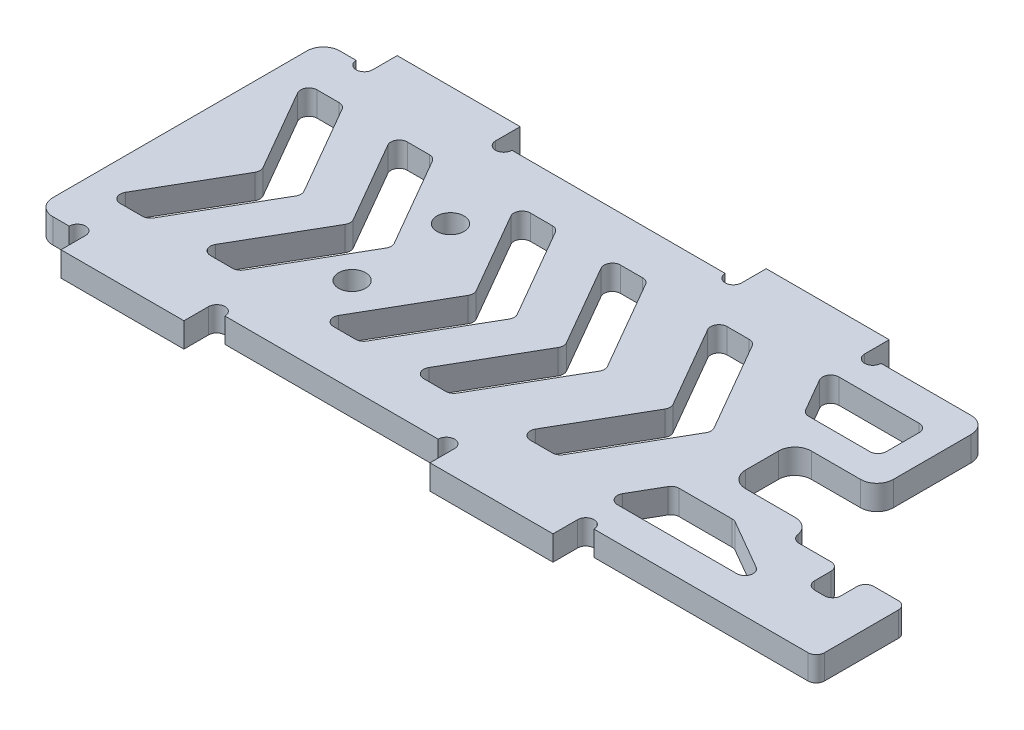
SolidWorks part; units mm, degrees
material "环氧树脂,未充填"
ref_plane "前视基准面" through (0, 0, 0) normal (0, 0, 1) x (1, 0, 0)
ref_plane "上视基准面" through (0, 0, 0) normal (0, 1, 0) x (1, 0, 0)
ref_plane "右视基准面" through (0, 0, 0) normal (1, 0, 0) x (0, 0, -1)
sketch "草图1" plane through (0, 0, 0) normal (0, 1, 0) x (1, 0, 0)
  line L0 (-30, 20.5) -> (-15, 20.5)
  line L1 (-15, 20.5) -> (-15, 17.5)
  line L2 (-15, 17.5) -> (15, 17.5)
  line L3 (15, 17.5) -> (15, 20.5)
  line L4 (15, 20.5) -> (30, 20.5)
  line L5 (30, 20.5) -> (30, 17.5)
  line L6 (30, 17.5) -> (43, 17.5)
  line L7 (45, 15.5) -> (45, -5.5)
  line L8 (46, -6.5) -> (49.9, -6.5)
  line L9 (50.9, -7.5) -> (50.9, -9.5)
  line L10 (51.9, -10.5) -> (53.1, -10.5)
  line L11 (54.1, -9.5) -> (54.1, -7.5)
  line L12 (55.1, -6.5) -> (58.1, -6.5)
  line L13 (59.1, -7.5) -> (59.1, -16.5)
  line L14 (58.1, -17.5) -> (30, -17.5)
  line L15 (30, -17.5) -> (30, -20.5)
  line L16 (30, -20.5) -> (15, -20.5)
  line L17 (15, -20.5) -> (15, -17.5)
  line L18 (15, -17.5) -> (-15, -17.5)
  line L19 (-15, -17.5) -> (-15, -20.5)
  line L20 (-15, -20.5) -> (-30, -20.5)
  line L21 (-30, -20.5) -> (-30, -17.5)
  line L22 (-30, -17.5) -> (-34, -17.5)
  line L23 (-36, -15.5) -> (-36, 15.5)
  line L24 (-34, 17.5) -> (-30, 17.5)
  line L25 (-30, 17.5) -> (-30, 20.5)
  line L26 (-1000, 0) -> (49000, 0) construction
  line L27 (-9, -6) -> (-9, 6) construction
  arc A0 (53.1, -10.5) -> (54.1, -9.5) centre (53.1, -9.5) ccw
  arc A1 (50.9, -9.5) -> (51.9, -10.5) centre (51.9, -9.5) ccw
  arc A2 (59.1, -16.5) -> (58.1, -17.5) centre (58.1, -16.5) cw
  arc A3 (58.1, -6.5) -> (59.1, -7.5) centre (58.1, -7.5) cw
  arc A4 (54.1, -7.5) -> (55.1, -6.5) centre (55.1, -7.5) cw
  arc A5 (45, -5.5) -> (46, -6.5) centre (46, -5.5) ccw
  circle A6 centre (-9, 6) radius 1.65
  circle A7 centre (-9, -6) radius 1.65
  arc A8 (-34, -17.5) -> (-36, -15.5) centre (-34, -15.5) cw
  arc A9 (-36, 15.5) -> (-34, 17.5) centre (-34, 15.5) cw
  arc A10 (43, 17.5) -> (45, 15.5) centre (43, 15.5) cw
  arc A11 (49.9, -6.5) -> (50.9, -7.5) centre (49.9, -7.5) cw
  point P29 (-9, 0)
  point P37 (0, -17.5)
  dimension "D6" = 1
  dimension "D8" = 1
  dimension "D14" = 1
  dimension "D16" = 3.3
  dimension "D18" = 2
  dimension "D19" = 1
  dimension "D1" = 15
  dimension "D2" = 30
  dimension "D3" = 3
  dimension "D4" = 11
  dimension "D5" = 7
  dimension "D7" = 5
  dimension "D9" = 17.5
  dimension "D10" = 6
  dimension "D11" = 15
  dimension "D12" = 5.9
  dimension "D13" = 3.2
  dimension "D15" = 12
  dimension "D17" = 9
  dimension "D20" = 30
  dimension "D21" = 3
  dimension "D22" = 36
  dimension "D23" = 17.5
  dimension "D24" = 15
  dimension "D25" = 0
extrude "凸台-拉伸1" add sketch "草图1" along normal blind 3
sketch "草图2" plane through (0, 3, 0) normal (0, 1, 0) x (1, 0, 0)
  line L0 (-201000, 0) -> (249000, 0) construction
  line L1 (37, -4) -> (45, -4)
  line L2 (35, -2) -> (35, 2)
  line L3 (37, 4) -> (45, 4)
  line L4 (45, -4) -> (45, 4)
  line L5 (35, -4) -> (45, 4) construction
  line L6 (35, 4) -> (45, -4) construction
  line L7 (45, 15.5) -> (45, -5.5) construction
  arc A0 (35, 2) -> (37, 4) centre (37, 2) cw
  arc A1 (37, -4) -> (35, -2) centre (37, -2) cw
  point P0 (40, 0)
  dimension "D3" = 2
  dimension "D1" = 8
  dimension "D2" = 10
extrude "切除-拉伸1" cut sketch "草图2" against normal blind 3
fillet "圆角1" radius 2 2 edges at (45, 1.5, 4) (45, 1.5, -4)
sketch "草图3" plane through (0, 3, 0) normal (0, 1, 0) x (1, 0, 0)
  line L0 (-30, 17.5) -> (-34, 17.5) construction
  line L1 (15, 17.5) -> (-15, 17.5) construction
  line L2 (0, -1000) -> (0, 49000) construction
  line L3 (-1000, 0) -> (49000, 0) construction
  line L4 (43, 17.5) -> (30, 17.5) construction
  line L5 (-34, -17.5) -> (-30, -17.5) construction
  line L6 (-15, -17.5) -> (15, -17.5) construction
  circle A0 centre (-31, 17.5) radius 1
  circle A1 centre (-14, 17.5) radius 1
  circle A8 centre (14, 17.5) radius 1
  circle A9 centre (31, 17.5) radius 1
  circle A10 centre (-31, -17.5) radius 1
  circle A11 centre (-14, -17.5) radius 1
  circle A12 centre (14, -17.5) radius 1
  circle A13 centre (31, -17.5) radius 1
  dimension "D1" = 2
extrude "切除-拉伸2" cut sketch "草图3" against normal blind 3
sketch "草图4" plane through (0, 3, 0) normal (0, 1, 0) x (1, 0, 0)
  line L0 (-1000, 0) -> (49000, 0) construction
  line L1 (-1007.3937, 12) -> (48992.6063, 12) construction
  line L2 (-999.8827, -12) -> (49000.1173, -12) construction
  line L3 (-15.3605, 0.5) -> (-21.134, 10.5)
  line L4 (-31.2679, 12) -> (-28.5774, 12)
  line L5 (-27.7113, 11.5) -> (-21.3605, 0.5)
  line L6 (-21.3605, -0.5) -> (-27.7113, -11.5)
  line L7 (-28.5774, -12) -> (-31.2679, -12)
  line L8 (-32.134, -10.5) -> (-26.3605, -0.5)
  line L9 (-26.3605, 0.5) -> (-32.134, 10.5)
  line L10 (-36, 15.5) -> (-36, -15.5) construction
  line L11 (-20.2679, 12) -> (-17.5774, 12)
  line L12 (-16.7113, 11.5) -> (-10.3605, 0.5)
  line L13 (-10.3605, -0.5) -> (-16.7113, -11.5)
  line L14 (-17.5774, -12) -> (-20.2679, -12)
  line L15 (-21.134, -10.5) -> (-15.3605, -0.5)
  line L16 (10.6395, 0.5) -> (4.866, 10.5)
  line L17 (5.7321, 12) -> (8.4226, 12)
  line L18 (9.2887, 11.5) -> (15.6395, 0.5)
  line L19 (15.6395, -0.5) -> (9.2887, -11.5)
  line L20 (8.4226, -12) -> (5.7321, -12)
  line L21 (4.866, -10.5) -> (10.6395, -0.5)
  line L22 (-0.3605, 0.5) -> (-6.134, 10.5)
  line L23 (-5.2679, 12) -> (-2.5774, 12)
  line L24 (-1.7113, 11.5) -> (4.6395, 0.5)
  line L25 (4.6395, -0.5) -> (-1.7113, -11.5)
  line L26 (-2.5774, -12) -> (-5.2679, -12)
  line L27 (-6.134, -10.5) -> (-0.3605, -0.5)
  line L28 (23.6395, 0.5) -> (17.866, 10.5)
  line L29 (18.7321, 12) -> (21.4226, 12)
  line L30 (22.2887, 11.5) -> (28.6395, 0.5)
  line L31 (28.6395, -0.5) -> (22.2887, -11.5)
  line L32 (21.4226, -12) -> (18.7321, -12)
  line L33 (17.866, -10.5) -> (23.6395, -0.5)
  line L34 (36.6395, 0.5) -> (30.866, 10.5) construction
  line L35 (31.7321, 12) -> (34.4226, 12) construction
  line L36 (35.2887, 11.5) -> (41.6395, 0.5) construction
  line L37 (41.6395, -0.5) -> (35.2887, -11.5) construction
  line L38 (34.4226, -12) -> (31.7321, -12) construction
  line L39 (30.866, -10.5) -> (36.6395, -0.5) construction
  line L40 (30.866, 13.5) -> (40.6395, 13.5)
  line L41 (41.6395, 12.5) -> (41.6395, 8.5)
  line L42 (40.6395, 7.5) -> (33.1754, 7.5)
  line L43 (32.3094, 8) -> (30, 12)
  line L44 (43, 17.5) -> (32, 17.5) construction
  line L46 (32.8868, -8) -> (39.3397, -8)
  line L47 (39.8397, -8.134) -> (45.9019, -11.634)
  line L48 (45.4019, -13.5) -> (30.866, -13.5)
  line L49 (32.0207, -8.5) -> (30, -12)
  line L50 (37, -4) -> (43.042, -4) construction
  line L51 (32, -17.5) -> (58.1, -17.5) construction
  arc A0 (-31.2679, -12) -> (-32.134, -10.5) centre (-31.2679, -11) cw
  arc A1 (-27.7113, -11.5) -> (-28.5774, -12) centre (-28.5774, -11) cw
  arc A2 (-21.3605, 0.5) -> (-21.3605, -0.5) centre (-22.2265, 0) cw
  arc A3 (-28.5774, 12) -> (-27.7113, 11.5) centre (-28.5774, 11) cw
  arc A4 (-31.2679, 12) -> (-32.134, 10.5) centre (-31.2679, 11) ccw
  arc A5 (-20.2679, 12) -> (-21.134, 10.5) centre (-20.2679, 11) ccw
  arc A6 (-17.5774, 12) -> (-16.7113, 11.5) centre (-17.5774, 11) cw
  arc A7 (-10.3605, 0.5) -> (-10.3605, -0.5) centre (-11.2265, 0) cw
  arc A8 (-16.7113, -11.5) -> (-17.5774, -12) centre (-17.5774, -11) cw
  arc A9 (-20.2679, -12) -> (-21.134, -10.5) centre (-20.2679, -11) cw
  arc A10 (5.7321, 12) -> (4.866, 10.5) centre (5.7321, 11) ccw
  arc A11 (8.4226, 12) -> (9.2887, 11.5) centre (8.4226, 11) cw
  arc A12 (15.6395, 0.5) -> (15.6395, -0.5) centre (14.7735, 0) cw
  arc A13 (9.2887, -11.5) -> (8.4226, -12) centre (8.4226, -11) cw
  arc A14 (5.7321, -12) -> (4.866, -10.5) centre (5.7321, -11) cw
  arc A15 (-5.2679, 12) -> (-6.134, 10.5) centre (-5.2679, 11) ccw
  arc A16 (-2.5774, 12) -> (-1.7113, 11.5) centre (-2.5774, 11) cw
  arc A17 (4.6395, 0.5) -> (4.6395, -0.5) centre (3.7735, 0) cw
  arc A18 (-1.7113, -11.5) -> (-2.5774, -12) centre (-2.5774, -11) cw
  arc A19 (-5.2679, -12) -> (-6.134, -10.5) centre (-5.2679, -11) cw
  arc A20 (18.7321, 12) -> (17.866, 10.5) centre (18.7321, 11) ccw
  arc A21 (21.4226, 12) -> (22.2887, 11.5) centre (21.4226, 11) cw
  arc A22 (28.6395, 0.5) -> (28.6395, -0.5) centre (27.7735, 0) cw
  arc A23 (22.2887, -11.5) -> (21.4226, -12) centre (21.4226, -11) cw
  arc A24 (18.7321, -12) -> (17.866, -10.5) centre (18.7321, -11) cw
  arc A25 (31.7321, 12) -> (30.866, 10.5) centre (31.7321, 11) ccw construction
  arc A26 (34.4226, 12) -> (35.2887, 11.5) centre (34.4226, 11) cw construction
  arc A27 (41.6395, 0.5) -> (41.6395, -0.5) centre (40.7735, 0) cw construction
  arc A28 (35.2887, -11.5) -> (34.4226, -12) centre (34.4226, -11) cw construction
  arc A29 (31.7321, -12) -> (30.866, -10.5) centre (31.7321, -11) cw construction
  arc A30 (-26.3605, -0.5) -> (-26.3605, 0.5) centre (-27.2265, 0) ccw
  arc A31 (36.6395, 0.5) -> (36.6395, -0.5) centre (35.7735, 0) cw construction
  arc A32 (23.6395, 0.5) -> (23.6395, -0.5) centre (22.7735, 0) cw
  arc A33 (10.6395, 0.5) -> (10.6395, -0.5) centre (9.7735, 0) cw
  arc A34 (-0.3605, 0.5) -> (-0.3605, -0.5) centre (-1.2265, 0) cw
  arc A35 (-15.3605, 0.5) -> (-15.3605, -0.5) centre (-16.2265, 0) cw
  arc A36 (33.1754, 7.5) -> (32.3094, 8) centre (33.1754, 8.5) cw
  arc A37 (41.6395, 8.5) -> (40.6395, 7.5) centre (40.6395, 8.5) cw
  arc A38 (40.6395, 13.5) -> (41.6395, 12.5) centre (40.6395, 12.5) cw
  arc A39 (30.866, 13.5) -> (30, 12) centre (30.866, 12.5) ccw
  arc A40 (39.3397, -8) -> (39.8397, -8.134) centre (39.3397, -9) cw
  arc A41 (45.9019, -11.634) -> (45.4019, -13.5) centre (45.4019, -12.5) cw
  arc A42 (30.866, -13.5) -> (30, -12) centre (30.866, -12.5) cw
  arc A43 (32.8868, -8) -> (32.0207, -8.5) centre (32.8868, -9) ccw
  point P17 (-33, -12)
  point P20 (-28, -12)
  point P23 (-21.0718, 0)
  point P26 (-28, 12)
  point P29 (-33, 12)
  point P112 (-26.0718, 0)
  point P131 (32.5981, 7.5)
  point P134 (41.6395, 7.5)
  point P137 (41.6395, 13.5)
  point P152 (49.134, -13.5)
  point P155 (29.134, -13.5)
  point P158 (32.3094, -8)
  dimension "D6" = 1
  dimension "D13" = 1
  dimension "D14" = 1
  dimension "D17" = 1
  dimension "D21" = 1
  dimension "D1" = 12
  dimension "D2" = 12
  dimension "D3" = 120
  dimension "D4" = 3
  dimension "D5" = 5
  dimension "D8" = 11
  dimension "D10" = 15
  dimension "D12" = 13
  dimension "D15" = 4
  dimension "D16" = 6
  dimension "D18" = 4
  dimension "D19" = 4
  dimension "D20" = 20
  dimension "D7" = 2
  dimension "D9" = 2
  dimension "D11" = 3
extrude "切除-拉伸3" cut sketch "草图4" against normal blind 3
